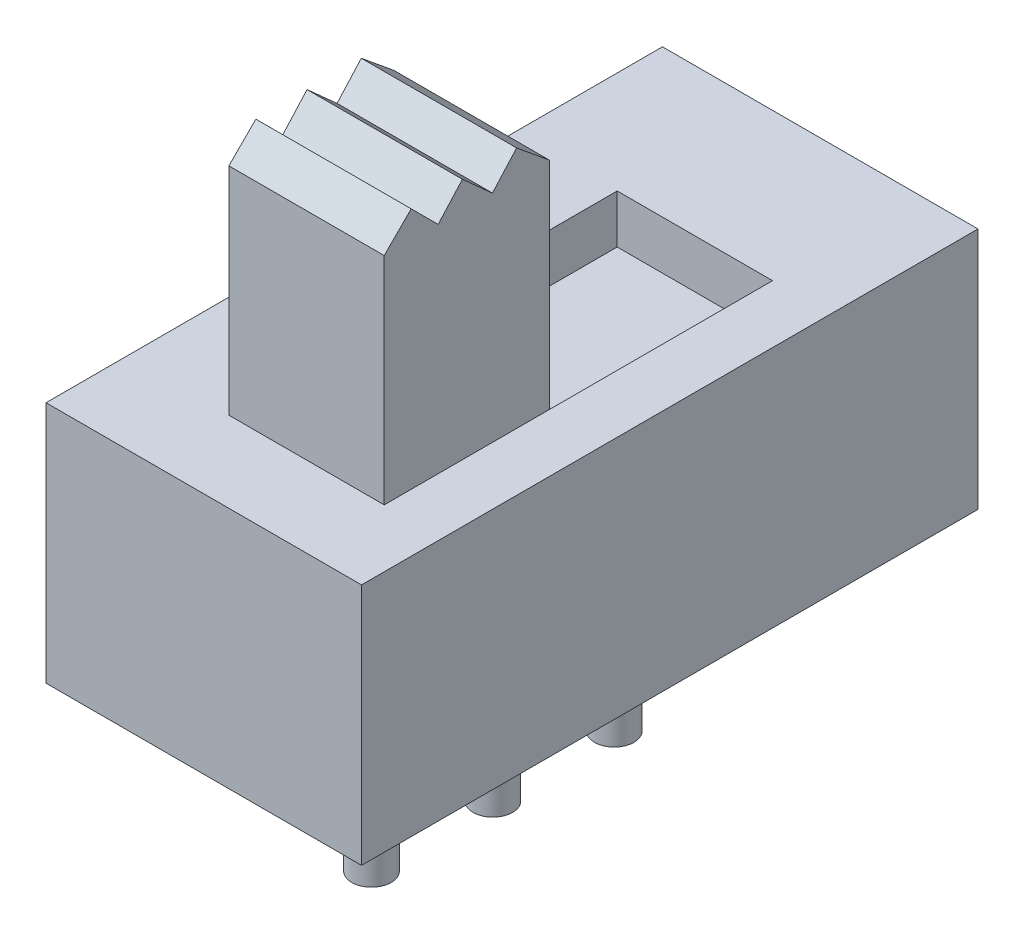
SolidWorks part; units mm, degrees
ref_plane "Front Plane" through (0, 0, 0) normal (0, 0, 1) x (1, 0, 0)
ref_plane "Top Plane" through (0, 0, 0) normal (0, 1, 0) x (1, 0, 0)
ref_plane "Right Plane" through (0, 0, 0) normal (1, 0, 0) x (0, 0, -1)
sketch "Sketch1" plane through (0, 0, 0) normal (0, 1, 0) x (1, 0, 0)
  line L1 (0, 0) -> (-6.5, 0)
  line L2 (0, 0) -> (0, 12.7)
  line L3 (0, 12.7) -> (-6.5, 12.7)
  line L4 (-6.5, 0) -> (-6.5, 12.7)
  dimension "D1" = 12.7
  dimension "D2" = 6.5
extrude "Boss-Extrude1" add sketch "Sketch1" along normal blind 5.0038
sketch "Sketch2" plane through (0, 5.0038, 0) normal (0, 1, 0) x (1, 0, 0)
  line L0 (0, 0) -> (0, 12.7) construction
  line L1 (-4.3942, 5.065) -> (-1.1938, 5.065)
  line L2 (-4.3942, 5.065) -> (-4.3942, 1.6614)
  line L3 (-4.3942, 1.6614) -> (-1.1938, 1.6614)
  line L4 (-1.1938, 5.065) -> (-1.1938, 1.6614)
  point P4 (-1.1938, 3.3632)
  dimension "D1" = 3.4036
  dimension "D2" = 3.2004
  dimension "D3" = 1.1938
extrude "Boss-Extrude2" add sketch "Sketch2" along normal blind 5.0038
sketch "Sketch3" plane through (0, 5.0038, 0) normal (0, 1, 0) x (1, 0, 0)
  line L0 (-1.1938, 1.6614) -> (-1.1938, 5.065) construction
  line L1 (-4.3942, 5.065) -> (-1.1938, 5.065)
  line L2 (-4.3942, 5.065) -> (-4.3942, 9.6614)
  line L3 (-4.3942, 9.6614) -> (-1.1938, 9.6614)
  line L4 (-1.1938, 5.065) -> (-1.1938, 9.6614)
  line L5 (-4.3942, 1.6614) -> (-1.1938, 1.6614) construction
  dimension "D1" = 0
  dimension "D2" = 8
extrude "Cut-Extrude1" cut sketch "Sketch3" against normal blind 1
sketch "Sketch4" plane through (-1.1938, 0, 0) normal (1, 0, 0) x (0, 0, -1)
  line L0 (1.6614, 9.4519) -> (2.2171, 10.0076)
  line L1 (1.6614, 10.0076) -> (1.6614, 5.0038) construction
  line L2 (1.6614, 10.0076) -> (5.065, 10.0076) construction
  line L3 (2.2171, 10.0076) -> (2.7728, 9.4519)
  line L4 (2.7728, 9.4519) -> (3.2718, 10.0076)
  line L5 (3.2718, 10.0076) -> (3.8907, 9.4519)
  line L6 (3.8907, 9.4519) -> (4.3897, 10.0076)
  line L7 (4.3897, 10.0076) -> (5.065, 9.4519)
  line L8 (5.065, 10.0076) -> (5.065, 5.0038) construction
  line L9 (5.065, 9.4519) -> (5.065, 10.0076)
  line L10 (5.065, 10.0076) -> (1.6614, 10.0076)
  line L11 (1.6614, 10.0076) -> (1.6614, 9.4519)
  line M2 (5.065, 5.0038) -> (5.065, 10.0076)
  line M3 (5.065, 10.0076) -> (1.6614, 10.0076)
  line M4 (1.6614, 10.0076) -> (1.6614, 5.0038)
extrude "Cut-Extrude2" cut sketch "Sketch4" against normal blind 11 contours L0 M4 M3 | L3 L4 M3 | L5 L6 M3 | L7 M3 M2
sketch "Sketch5" plane through (0, 0, 0) normal (0, -1, 0) x (-1, 0, 0)
  line L0 (0, 0) -> (0, 12.7) construction
  line L1 (6.5, 0) -> (0, 0) construction
  circle A0 centre (2.794, 3) radius 0.4064
  circle A1 centre (2.794, 5.5) radius 0.4064
  circle A2 centre (2.794, 8) radius 0.4064
  dimension "D1" = 0.8128
  dimension "D2" = 2.794
  dimension "D4" = 3
  dimension "D3" = 3
extrude "Boss-Extrude3" add sketch "Sketch5" along normal blind 3
